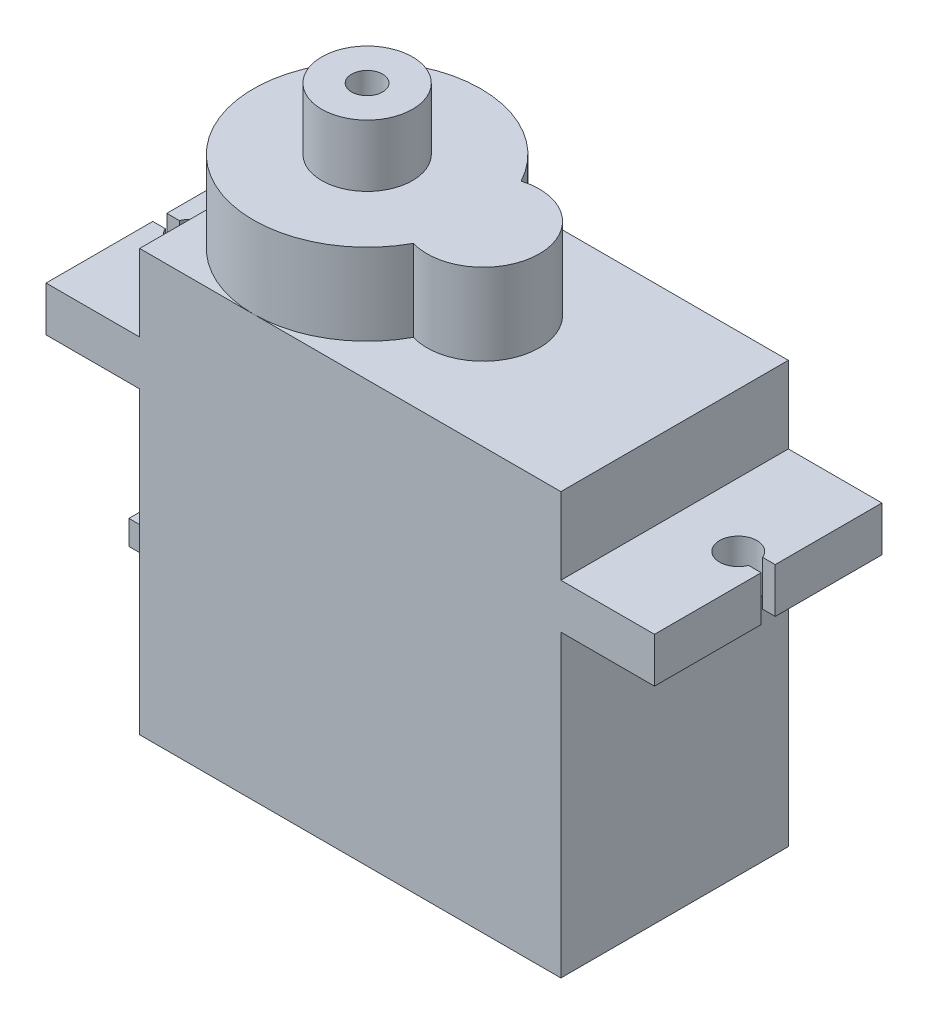
SolidWorks part; units mm, degrees
ref_plane "Front Plane" through (0, 0, 0) normal (0, 0, 1) x (1, 0, 0)
ref_plane "Top Plane" through (0, 0, 0) normal (0, 1, 0) x (1, 0, 0)
ref_plane "Right Plane" through (0, 0, 0) normal (1, 0, 0) x (0, 0, -1)
sketch "Sketch1" plane through (0, 0, 0) normal (0, 0, 1) x (1, 0, 0)
  line L0 (0, 0) -> (0, 11.25) construction
  line L1 (-11.25, -11.25) -> (11.25, -11.25)
  line L2 (-11.25, -11.25) -> (-11.25, 4.75)
  line L3 (-11.25, 11.25) -> (11.25, 11.25)
  line L4 (11.25, -11.25) -> (11.25, 4.75)
  line L5 (-11.25, -11.25) -> (11.25, 11.25) construction
  line L6 (-11.25, 11.25) -> (11.25, -11.25) construction
  line L7 (11.25, 7.15) -> (16.25, 7.15)
  line L9 (11.25, 4.75) -> (16.25, 4.75)
  line L10 (16.25, 7.15) -> (16.25, 4.75)
  line L11 (-11.25, 4.75) -> (-16.25, 4.75)
  line L12 (-16.25, 7.15) -> (-16.25, 4.75)
  line L13 (-11.25, 7.15) -> (-16.25, 7.15)
  line L15 (11.25, 7.15) -> (11.25, 11.25)
  line L16 (-11.25, 7.15) -> (-11.25, 11.25)
  point P0 (0, 0)
  dimension "D1" = 22.5
  dimension "D2" = 22.5
  dimension "D3" = 16
  dimension "D4" = 2.4
  dimension "D5" = 5
extrude "Boss-Extrude1" add sketch "Sketch1" along normal blind 12.15
sketch "Sketch4" plane through (0, 11.25, 0) normal (0, 1, 0) x (1, 0, 0)
  line L0 (-11.25, -6.075) -> (11.25, -6.075) construction
  line L1 (-11.25, -12.15) -> (-11.25, 0) construction
  line L2 (11.25, -12.15) -> (11.25, 0) construction
  line L3 (-5.175, 0) -> (-5.175, -12.15) construction
  line L4 (11.25, 0) -> (-11.25, 0) construction
  line L5 (11.25, -12.15) -> (-11.25, -12.15) construction
  arc A0 (0.1755, -3.1978) -> (0.1755, -8.9522) centre (-5.175, -6.075) ccw
  arc A1 (0.1755, -8.9522) -> (0.1755, -3.1978) centre (1.025, -6.075) ccw
  dimension "D2" = 6
  dimension "D3" = 6.2
  dimension "D1" = 6.075
extrude "Boss-Extrude2" add sketch "Sketch4" along normal blind 4.35
sketch "Sketch5" plane through (0, 15.6, 0) normal (0, 1, 0) x (1, 0, 0)
  circle A0 centre (-5.175, -6.075) radius 2.425
  dimension "D1" = 4.85
extrude "Boss-Extrude3" add sketch "Sketch5" along normal blind 3.3
sketch "Sketch6" plane through (0, 18.9, 0) normal (0, 1, 0) x (1, 0, 0)
  circle A0 centre (-5.175, -6.075) radius 0.8282
extrude "Cut-Extrude3" cut sketch "Sketch6" against normal blind 4
sketch "Sketch8" plane through (0, 7.15, 0) normal (0, 1, 0) x (1, 0, 0)
  line L0 (-16.25, -6.075) -> (-11.25, -6.075) construction
  line L1 (-16.25, -12.15) -> (-16.25, 0) construction
  line L2 (-11.25, -12.15) -> (-11.25, 0) construction
  line L3 (-11.25, -6.075) -> (11.25, -6.075) construction
  line L4 (11.25, -12.15) -> (11.25, 0) construction
  line L5 (11.25, -6.075) -> (16.25, -6.075) construction
  line L6 (16.25, -12.15) -> (16.25, 0) construction
  circle A0 centre (-14.65, -6.075) radius 1
  circle A1 centre (14.65, -6.075) radius 1
  dimension "D1" = 2
  dimension "D2" = 2
  dimension "D3" = 1.6
  dimension "D4" = 1.6
extrude "Cut-Extrude4" cut sketch "Sketch8" against normal blind 5
sketch "Sketch9" plane through (0, 7.15, 0) normal (0, 1, 0) x (1, 0, 0)
  line L0 (-16.25, -6.075) -> (-11.25, -6.075) construction
  line L1 (-16.25, -12.15) -> (-16.25, 0) construction
  line L2 (-11.25, -6.075) -> (11.25, -6.075) construction
  line L3 (11.25, -12.15) -> (11.25, 0) construction
  line L4 (11.25, -6.075) -> (16.25, -6.075) construction
  line L5 (16.25, -12.15) -> (16.25, 0) construction
  line L7 (-17.236, -5.7) -> (-15.0702, -5.7)
  line L8 (-17.236, -5.7) -> (-17.236, -6.45)
  line L9 (-17.236, -6.45) -> (-15.0702, -6.45)
  line L10 (-15.0702, -5.7) -> (-15.0702, -6.45)
  line L11 (15.1718, -5.7) -> (16.9017, -5.7)
  line L12 (15.1718, -5.7) -> (15.1718, -6.45)
  line L13 (15.1718, -6.45) -> (16.9017, -6.45)
  line L14 (16.9017, -5.7) -> (16.9017, -6.45)
  arc A0 (0.1755, -3.1978) -> (0.1755, -8.9522) centre (-5.175, -6.075) ccw construction
  dimension "D1" = 0.75
  dimension "D2" = 0.75
  dimension "D3" = 0.375
  dimension "D4" = 0.375
extrude "Cut-Extrude5" cut sketch "Sketch9" against normal blind 5
sketch "Sketch10" plane through (11.25, 0, 0) normal (1, 0, 0) x (0, 0, -1)
  line L0 (-6.075, -11.25) -> (-6.075, 4.75) construction
  line L1 (-12.15, -11.25) -> (0, -11.25) construction
  line L2 (-7.075, 4.75) -> (-5.075, 4.75) construction
  line L4 (-7.725, -5.95) -> (-4.425, -5.95)
  line L5 (-7.725, -5.95) -> (-7.725, -7.25)
  line L6 (-7.725, -7.25) -> (-4.425, -7.25)
  line L7 (-4.425, -5.95) -> (-4.425, -7.25)
  dimension "D1" = 1.3
  dimension "D2" = 3.3
  dimension "D3" = 1.65
  dimension "D4" = 4
extrude "Boss-Extrude6" add sketch "Sketch10" against normal blind 27.5
